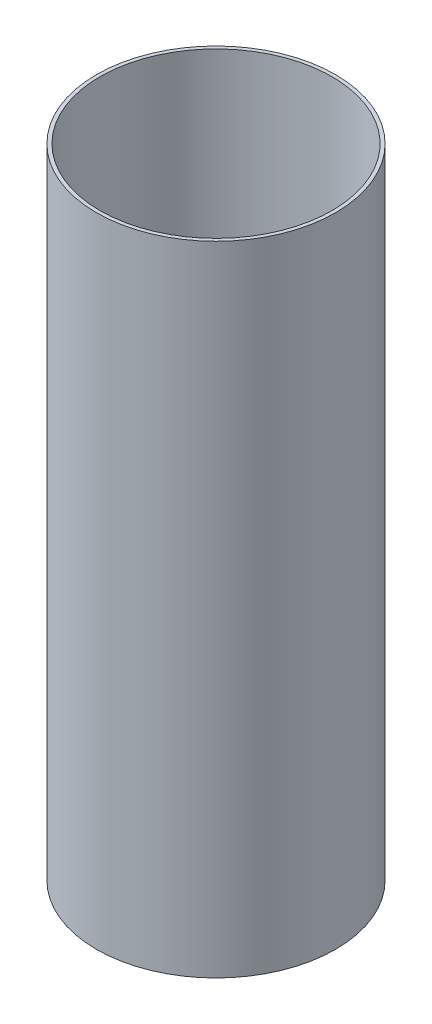
SolidWorks part; units mm, degrees
material "C-Glass Fiber"
ref_plane "Front Plane" through (0, 0, 0) normal (0, 0, 1) x (1, 0, 0)
ref_plane "Top Plane" through (0, 0, 0) normal (0, 1, 0) x (1, 0, 0)
ref_plane "Right Plane" through (0, 0, 0) normal (1, 0, 0) x (0, 0, -1)
sketch "Sketch1" plane through (0, 0, 0) normal (0, 1, 0) x (1, 0, 0)
  circle A0 centre (0, 0) radius 73.914
  circle A1 centre (0, 0) radius 76.1746
  dimension "D1" = 152.3492
  dimension "D2" = 147.828
extrude "Boss-Extrude1" add sketch "Sketch1" along normal blind 406.4
